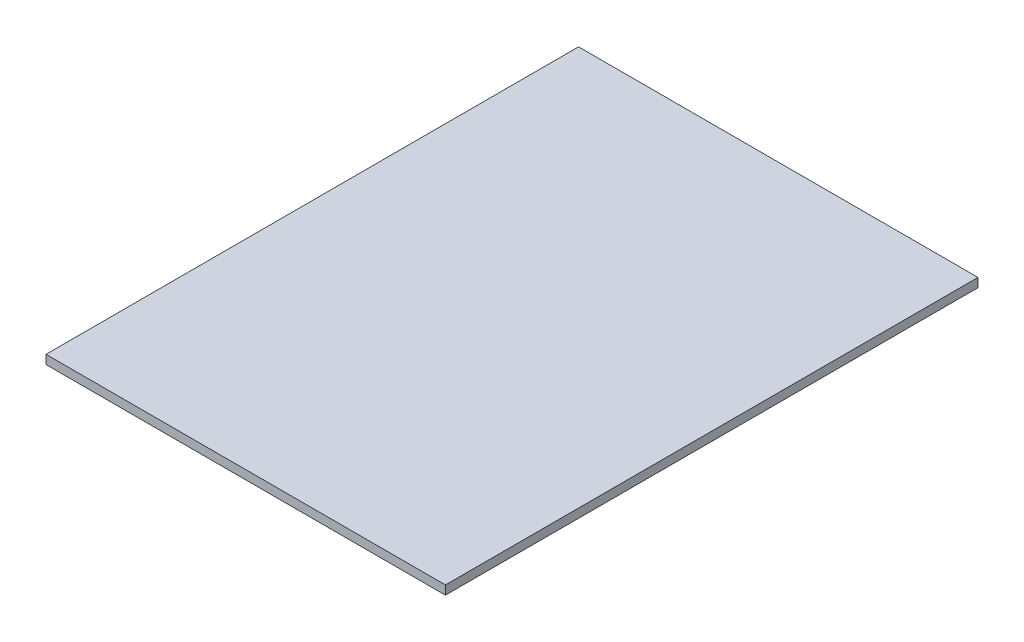
SolidWorks part; units mm, degrees
ref_plane "Plano frontal" through (0, 0, 0) normal (0, 0, 1) x (1, 0, 0)
ref_plane "Plano superior" through (0, 0, 0) normal (0, 1, 0) x (1, 0, 0)
ref_plane "Plano direito" through (0, 0, 0) normal (1, 0, 0) x (0, 0, -1)
sketch "Esboço1" plane through (0, 0, 0) normal (0, 1, 0) x (1, 0, 0)
  line L0 (0, 0) -> (0, 360)
  line L1 (0, 360) -> (-270, 360)
  line L2 (-270, 360) -> (-270, 0)
  line L3 (-270, 0) -> (0, 0)
  dimension "D1" = 360
  dimension "D2" = 270
extrude "Ressalto-extrusão1" add sketch "Esboço1" along normal blind 6
